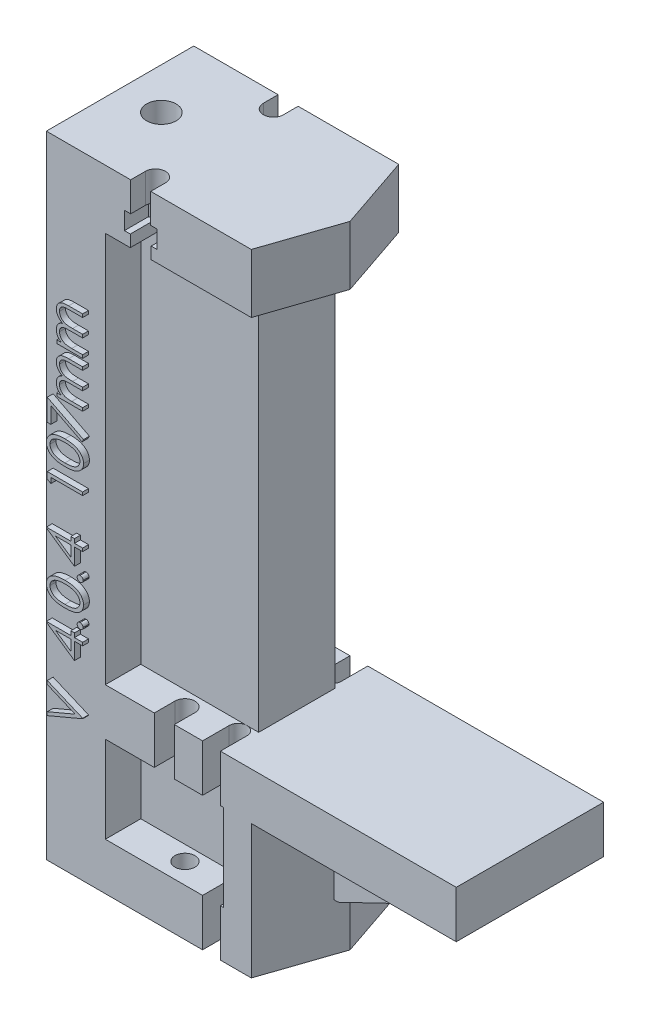
SolidWorks part; units mm, degrees
material "ABS"
ref_plane "Front" through (0, 0, 0) normal (0, 0, 1) x (1, 0, 0)
ref_plane "Top" through (0, 0, 0) normal (0, 1, 0) x (1, 0, 0)
ref_plane "Right" through (0, 0, 0) normal (1, 0, 0) x (0, 0, -1)
sketch "Sketch6" plane through (0, 0, 0) normal (0, 0, 1) x (1, 0, 0)
  line L0 (-25, 53.5) -> (15, 53.5)
  line L1 (15, 53.5) -> (15, 45.5)
  line L2 (15, 45.5) -> (-15, 45.5)
  line L3 (-15, 45.5) -> (-15, -45.5)
  line L4 (-15, -45.5) -> (25, -45.5)
  line L5 (25, -45.5) -> (25, -53.5)
  line L6 (25, -53.5) -> (-25, -53.5)
  line L7 (-25, -53.5) -> (-25, 53.5)
  line L8 (-25, 53.5) -> (25, -53.5) construction
  dimension "D1" = 107
  dimension "D2" = 8
  dimension "D4" = 50
  dimension "D5" = 40
extrude "Boss-Extrude2" add sketch "Sketch6" along normal mid plane 25
sketch "Sketch15" plane through (0, 0, 12.5) normal (0, 0, 1) x (1, 0, 0)
  line L0 (-15, -22.805) -> (15, -22.805)
  line L1 (-15, -45.5) -> (-15, 45.5) construction
  line L2 (-15, -30.805) -> (5, -30.805)
  line L3 (5, -53.5) -> (15, -53.5)
  line L4 (15, -53.5) -> (15, -22.805)
  line L5 (-25, -53.5) -> (25, -53.5) construction
  line L6 (-15, -30.805) -> (-15, -22.805)
  line L7 (5, -53.5) -> (5, -30.805)
  dimension "D2" = 8
extrude "Boss-Extrude3" add sketch "Sketch15" against normal up to surface (25 mm away) up to face at (0, 0, -12.5)
sketch "Sketch20" plane through (0, 53.5, 0) normal (0, 1, 0) x (1, 0, 0)
  line L0 (-10.7, 12.5) -> (-10.7, 10)
  line L1 (15, 12.5) -> (-25, 12.5) construction
  line L2 (-7.3, 10) -> (-7.3, 12.5)
  line L3 (-7.3, 12.5) -> (-10.7, 12.5)
  line L4 (0, 0) -> (15, 0) construction
  line L5 (15, -12.5) -> (15, 12.5) construction
  line L6 (-7.3, -12.5) -> (-10.7, -12.5)
  line L7 (-7.3, -10) -> (-7.3, -12.5)
  line L8 (-10.7, -12.5) -> (-10.7, -10)
  line L9 (-9, -10) -> (-9, 10) construction
  arc A0 (-10.7, 10) -> (-7.3, 10) centre (-9, 10) ccw
  arc A1 (-10.7, -10) -> (-7.3, -10) centre (-9, -10) cw
  dimension "D1" = 1.7
  dimension "D2" = 20
extrude "Cut-Extrude2" cut sketch "Sketch20" against normal up to next
sketch "Sketch21" plane through (0, -53.5, 0) normal (0, -1, 0) x (1, 0, 0)
  line L0 (-6.7, 12.5) -> (-6.7, 9)
  line L1 (-25, 12.5) -> (25, 12.5) construction
  line L2 (-3.3, 9) -> (-3.3, 12.5)
  line L3 (-3.3, 12.5) -> (-6.7, 12.5) construction
  line L4 (-5, -9) -> (-5, 9) construction
  line L5 (-6.7, 12.5) -> (-3.3, 12.5)
  line L7 (-3.3, -12.5) -> (-6.7, -12.5)
  line L8 (-3.3, -9) -> (-3.3, -12.5)
  line L9 (-6.7, -12.5) -> (-6.7, -9)
  arc A0 (-6.7, 9) -> (-3.3, 9) centre (-5, 9) ccw
  arc A1 (-6.7, -9) -> (-3.3, -9) centre (-5, -9) cw
  dimension "D1" = 1.7
  dimension "D2" = 18
extrude "Cut-Extrude3" cut sketch "Sketch21" against normal up to surface (30.695 mm away) up to face at (0, -22.805, 0)
sketch "Sketch22" plane through (0, 0, 0) normal (0, 0, 1) x (1, 0, 0)
  line L0 (-15, 21.805) -> (11, 45.5)
  line L1 (-7.3, 45.5) -> (15, 45.5) construction
  line L2 (-15, 45.5) -> (11, 45.5)
  line L5 (-15, -22.805) -> (-15, 45.5) construction
  line L7 (-15, 45.5) -> (-10.7, 45.5) construction
  line L8 (-15, 45.5) -> (-15, 21.805)
extrude "Boss-Extrude5" [suppressed] add sketch "Sketch22" along normal mid plane 4
sketch "Sketch23" plane through (0, 53.5, 0) normal (0, 1, 0) x (1, 0, 0)
  line L0 (-2.51, 12.5) -> (-2.51, 9)
  line L1 (15, 12.5) -> (-7.3, 12.5) construction
  line L2 (0.51, 9) -> (0.51, 12.5)
  line L3 (0.51, 12.5) -> (-2.51, 12.5)
  line L4 (-9, 10) -> (-1, 10) construction
  line L5 (-1, 10) -> (-1, 9) construction
  line L6 (0, 0) -> (12, 0) construction
  line L8 (0.51, -12.5) -> (-2.51, -12.5)
  line L9 (0.51, -9) -> (0.51, -12.5)
  line L10 (-2.51, -12.5) -> (-2.51, -9)
  line L11 (15, -12.5) -> (15, 12.5) construction
  arc A0 (-2.51, 9) -> (0.51, 9) centre (-1, 9) ccw
  arc A1 (-2.51, -9) -> (0.51, -9) centre (-1, -9) cw
  dimension "D1" = 1.51
  dimension "D2" = 8
  dimension "D3" = 1
  dimension "D4" = 3
extrude "Cut-Extrude4" [suppressed] cut sketch "Sketch23" against normal up to next
sketch "Sketch24" plane through (0, -53.5, 0) normal (0, -1, 0) x (1, 0, 0)
  line L0 (1.49, -12.5) -> (1.49, -8)
  line L1 (-3.3, -12.5) -> (25, -12.5) construction
  line L2 (4.51, -8) -> (4.51, -12.5)
  line L3 (4.51, -12.5) -> (1.49, -12.5)
  line L4 (3, -8) -> (3, -9) construction
  line L5 (3, -9) -> (-5, -9) construction
  line L9 (4.51, 12.5) -> (1.49, 12.5)
  line L10 (4.51, 8) -> (4.51, 12.5)
  line L11 (1.49, 12.5) -> (1.49, 8)
  arc A0 (1.49, -8) -> (4.51, -8) centre (3, -8) cw
  arc A1 (1.49, 8) -> (4.51, 8) centre (3, 8) ccw
  dimension "D2" = 8
  dimension "D3" = 1
extrude "Cut-Extrude6" cut sketch "Sketch24" against normal up to surface (30.695 mm away) up to face at (-3.3333, -22.805, 0)
sketch "Sketch28" plane through (0, 53.5, 0) normal (0, 1, 0) x (1, 0, 0)
  line L0 (-10.7, 10) -> (-7.3, 10) construction
  line L1 (-10.7, -10) -> (-7.3, -10) construction
  line L2 (-7.3, -12.5) -> (-7.3, -10) construction
  arc A0 (-10.7, 10) -> (-7.3, 10) centre (-9, 10) ccw construction
  arc A1 (-7.3, -10) -> (-10.7, -10) centre (-9, -10) ccw construction
sketch "Sketch29" plane through (-25, 0, 0) normal (-1, 0, 0) x (0, 0, 1)
  line L0 (-12.5, 53.5) -> (12.5, 53.5)
  line L1 (12.5, 53.5) -> (12.5, -53.5)
  line L2 (12.5, -53.5) -> (-12.9424, -53.5)
  line L3 (-12.9424, -53.5) -> (-12.5, 53.5)
extrude "Cut-Extrude7" [suppressed] cut sketch "Sketch29" against normal blind 6
sketch "Sketch30" plane through (0, -45.5, 0) normal (0, 1, 0) x (1, 0, 0)
  line L0 (25, 12.5) -> (25, -12.5)
  line L1 (25, -12.5) -> (15, -12.5)
  line L2 (15, -12.5) -> (15, 12.5)
  line L3 (15, 12.5) -> (25, 12.5)
extrude "Cut-Extrude8" cut sketch "Sketch30" against normal up to surface (8 mm away) up to face at (-0.8, -53.5, 0)
sketch "Sketch34" plane through (0, -22.805, 0) normal (0, 1, 0) x (1, 0, 0)
  line L1 (9.755, 12.5) -> (14, 0)
  line L2 (15, -12.5) -> (4.51, -12.5) construction
  line L3 (9.755, -12.5) -> (15, -12.5)
  line L6 (15, 12.5) -> (9.755, 12.5)
  line L7 (15, 12.5) -> (4.51, 12.5) construction
  line L9 (15, -12.5) -> (15, 12.5)
  line L10 (15, 0) -> (14, 0) construction
  line L11 (14, 0) -> (9.755, -12.5)
extrude "Cut-Extrude9" cut sketch "Sketch34" against normal through all both and the other way through all
sketch "Sketch35" plane through (0, 0, 12.5) normal (0, 0, 1) x (1, 0, 0)
  line L0 (-17.85, 53.5) -> (-17.85, -53.5) construction
  line L1 (-10.7, 53.5) -> (-25, 53.5) construction
  line L2 (-25, -53.5) -> (-6.7, -53.5) construction
  text T0 "V  4.0.4  107mm" font "Century Gothic" height 6
extrude "Boss-Extrude6" add sketch "Sketch35" along normal blind 1
sketch3d "3DSketch1"
  line L0 (4.51, -22.805, 12.5) -> (4.51, -30.805, 12.5)
  line L1 (4.51, -30.805, 12.5) -> (4.51, -30.805, -12.5)
  line L2 (4.51, -30.805, -12.5) -> (4.51, -22.805, -12.5)
  line L3 (4.51, -22.805, -12.5) -> (4.51, -22.805, 12.5)
extrude "Boss-Extrude7" add sketch "3DSketch1" along direction (1, 0, 0) on the side against the normal blind 40
sketch "Sketch37" plane through (0, 0, 0) normal (0, 0, 1) x (1, 0, 0)
  line L1 (14, -30.805) -> (44.51, -30.805)
  line L3 (5, -45.5) -> (14, -45.5) construction
  line L4 (14, -30.805) -> (14, -45.5)
  line L5 (14, -45.5) -> (44.51, -30.805)
extrude "Boss-Extrude17" add sketch "Sketch37" along direction (0, 0, 1) on the side of the normal mid plane 4 separate body
sketch "Sketch38" plane through (0, 45.5, 0) normal (0, -1, 0) x (1, 0, 0)
  line L0 (-11.75, 11.5877) -> (-11.75, 12.5) construction
  line L1 (-10.7, 10) -> (-7.3, 10) construction
  line L2 (-6.25, 8.4123) -> (-6.25, 11.5877) construction
  line L3 (-9, 6.8246) -> (-6.25, 8.4123)
  line L4 (-11.75, 8.4123) -> (-9, 6.8246)
  line L5 (-11.75, 11.5877) -> (-11.75, 8.4123) construction
  line L6 (-9, 13.1754) -> (-11.75, 11.5877) construction
  line L7 (-6.25, 11.5877) -> (-9, 13.1754) construction
  line L8 (-10.7, -10) -> (-7.3, -10) construction
  line L9 (-6.25, -11.5877) -> (-6.25, -8.4123) construction
  line L10 (-6.25, -8.4123) -> (-9, -6.8246)
  line L11 (-9, -6.8246) -> (-11.75, -8.4123)
  line L12 (-11.75, -8.4123) -> (-11.75, -11.5877) construction
  line L13 (-11.75, -11.5877) -> (-9, -13.1754) construction
  line L14 (-9, -13.1754) -> (-6.25, -11.5877) construction
  line L15 (-15, 12.5) -> (-10.7, 12.5) construction
  line L17 (-7.3, 12.5) -> (9.755, 12.5) construction
  line L18 (-6.25, 12.5) -> (-6.25, 11.5877) construction
  line L19 (-11.75, -11.5877) -> (-11.75, -12.5) construction
  line L20 (-15, -12.5) -> (-10.7, -12.5) construction
  line L21 (-11.77, -12.5) -> (-6.23, -12.5)
  line L22 (-7.3, -12.5) -> (9.755, -12.5) construction
  line L23 (-6.25, -12.5) -> (-6.25, -11.5877) construction
  line L24 (-11.77, 12.5) -> (-11.77, 8.4238)
  line L25 (-11.77, 8.4238) -> (-11.75, 8.4123)
  line L26 (-6.23, 12.5) -> (-6.23, 8.4238)
  line L27 (-6.23, 8.4238) -> (-6.25, 8.4123)
  line L28 (-11.77, 12.5) -> (-6.23, 12.5)
  line L29 (-6.25, -8.4123) -> (-6.23, -8.4238)
  line L30 (-6.23, -8.4238) -> (-6.23, -12.5)
  line L31 (-11.77, -12.5) -> (-11.77, -8.4238)
  line L32 (-11.77, -8.4238) -> (-11.75, -8.4123)
  circle A1 centre (-9, 10) radius 2.75 construction
  circle A2 centre (-9, 10) radius 3.1754 construction
  circle A3 centre (-9, -10) radius 3.1754 construction
  circle A4 centre (-9, -10) radius 2.75 construction
  point P18 (-6.25, -10)
  point P19 (-9, 10)
  point P24 (-7.625, -7.6184)
  point P25 (-10.375, -7.6184)
  dimension "D1" = 5.5
  dimension "D2" = 6
  dimension "D3" = 6.3509
  dimension "D4" = 5.5
  dimension "D5" = 6.3509
  dimension "D7" = 0.02
  dimension "D8" = 0.02
  dimension "D9" = 0.02
extrude "Cut-Extrude10" cut sketch "Sketch38" against normal blind 3
sketch "Sketch39" plane through (14, 0, 0) normal (-1, 0, 0) x (0, 0, 1)
  line L1 (-2, -45.5) -> (2, -45.5)
  line L2 (-2, -45.5) -> (-2, -30.805)
  line L3 (-2, -30.805) -> (2, -30.805)
  line L4 (2, -45.5) -> (2, -30.805)
extrude "Boss-Extrude18" add sketch "Sketch39" along normal blind 2.5
hole_wizard "Ø5.0mm Dowel Hole1" positions "Sketch41" profile "Sketch42" hole size "Ø5.0" standard "ANSI Metric"
sketch "Sketch41" plane through (0, 53.5, 0) normal (0, 1, 0) x (1, 0, 0)
  line L0 (-25, 0) -> (-18, 0) construction
  line L1 (-25, -12.5) -> (-25, 12.5) construction
  point P0 (-18, 0)
  dimension "D1" = 7
sketch "Sketch42" plane through (-18, 53.5, 0) normal (1, 0, 0) x (0, 0, 1)
  line L0 (0, 0) -> (0, 6.5022)
  line L1 (0, 6.5022) -> (2.5, 5)
  line L2 (2.5, 5) -> (2.5, 0)
  line L5 (2.5, 0) -> (0, 0)
  line L10 (0, 6.5022) -> (-2.5, 5) construction
  line L11 (0, -6.35) -> (0, 107.95) construction
  dimension "Hole Dia." = 5
  dimension "Hole Depth" = 5
  dimension "Drill Angle" = 118
sketch "Sketch43" plane through (0, 45.5, 0) normal (0, -1, 0) x (1, 0, 0)
  line L0 (-11.77, 12.5) -> (-10.77, 12.5)
  line L1 (-10.77, 12.5) -> (-10.77, 7.8465)
  line L2 (-6.23, 12.5) -> (-7.23, 12.5)
  line L3 (-7.23, 12.5) -> (-7.23, 7.8465)
  line L4 (-11.77, -12.5) -> (-10.77, -12.5)
  line L5 (-10.77, -12.5) -> (-10.77, -7.8465)
  line L6 (-6.23, -12.5) -> (-7.23, -12.5)
  line L7 (-7.23, -12.5) -> (-7.23, -7.8465)
  line L8 (5, 2) -> (5, -2)
  line L19 (-15, -12.5) -> (-11.77, -12.5)
  line L20 (-11.77, 8.4238) -> (-11.77, 12.5)
  line L21 (-11.77, -8.4238) -> (-9, -6.8246)
  line L22 (-9, -6.8246) -> (-6.23, -8.4238)
  line L23 (-11.77, 8.4238) -> (-11.77, 12.5)
  line L24 (-6.23, -12.5) -> (9.755, -12.5)
  line L25 (9.755, -12.5) -> (14, 0)
  line L26 (14, 0) -> (9.755, 12.5)
  line L27 (9.755, 12.5) -> (-6.23, 12.5)
  line L28 (-11.77, -12.5) -> (-11.77, -8.4238)
  line L29 (-6.23, 8.4238) -> (-9, 6.8246)
  line L30 (-9, 6.8246) -> (-11.77, 8.4238)
  line L31 (-11.77, -12.5) -> (-11.77, -8.4238)
  line L32 (-11.77, 12.5) -> (-15, 12.5)
  line L33 (-15, 12.5) -> (-15, -12.5)
  line L38 (-15, -12.5) -> (-11.77, -12.5)
  line L40 (-11.77, -8.4238) -> (-9, -6.8246)
  line L41 (-9, -6.8246) -> (-6.23, -8.4238)
  line L43 (-6.23, -12.5) -> (9.755, -12.5)
  line L44 (9.755, -12.5) -> (14, 0)
  line L45 (14, 0) -> (9.755, 12.5)
  line L46 (9.755, 12.5) -> (-6.23, 12.5)
  line L48 (-6.23, 8.4238) -> (-9, 6.8246)
  line L49 (-9, 6.8246) -> (-11.77, 8.4238)
  line L51 (-11.77, 12.5) -> (-15, 12.5)
  line L52 (-15, 12.5) -> (-15, -12.5)
  line L57 (-6.23, -8.4238) -> (-6.23, -12.5)
  line L58 (-6.23, -8.4238) -> (-6.23, -12.5)
  line L59 (-6.23, 12.5) -> (-6.23, 8.4238)
  line L60 (-6.23, 12.5) -> (-6.23, 8.4238)
  dimension "D2" = 1
  dimension "D3" = 1
  dimension "D4" = 1
  dimension "D5" = 1
  dimension "D1" = 0
extrude "Boss-Extrude19" add sketch "Sketch43" along normal blind 2
sketch "Sketch44" plane through (0, -53.5, 0) normal (0, -1, 0) x (1, 0, 0)
  line L0 (-6.7, -9) -> (-6.7, -12.5)
  line L1 (-6.7, -12.5) -> (-3.3, -12.5)
  line L2 (-3.3, -12.5) -> (-3.3, -9)
  line L3 (-6.7, 9) -> (-6.7, 12.5)
  line L4 (-6.7, 12.5) -> (-3.3, 12.5)
  line L5 (-3.3, 12.5) -> (-3.3, 9)
  circle A0 centre (-5, -9) radius 1.7
  circle A1 centre (-5, 9) radius 1.7
  line M8 (-3.3, 12.5) -> (-3.3, 9)
  line M10 (-6.7, 9) -> (-6.7, 12.5)
  line M14 (-6.7, -12.5) -> (-6.7, -9)
  line M16 (-3.3, -9) -> (-3.3, -12.5)
extrude "Boss-Extrude20" add sketch "Sketch44" against normal up to surface (8 mm away) contours A1 L4 M8 M10 | A0 L1 M14 M16 up to face at (-1.8, -45.5, 0)
sketch "Sketch45" plane through (0, -22.805, 0) normal (0, 1, 0) x (1, 0, 0)
  line L0 (-15, 12.5) -> (-15, -12.5) construction
  line L1 (-15, -6.49) -> (5, -6.49)
  line L2 (-15, -6.49) -> (-15, 6.49)
  line L3 (-15, 6.49) -> (5, 6.49)
  line L4 (5, -6.49) -> (5, 6.49)
  line L5 (5, -6.49) -> (5, 6.49) construction
  line L7 (5, -12.5) -> (5, 12.5) construction
  arc A0 (1.49, 8) -> (4.51, 8) centre (3, 8) ccw construction
  arc A1 (4.51, -8) -> (1.49, -8) centre (3, -8) ccw construction
extrude "Boss-Extrude21" add sketch "Sketch45" along normal up to next and the other way up to surface other way up to face at (0.3333, -45.5, 0)
